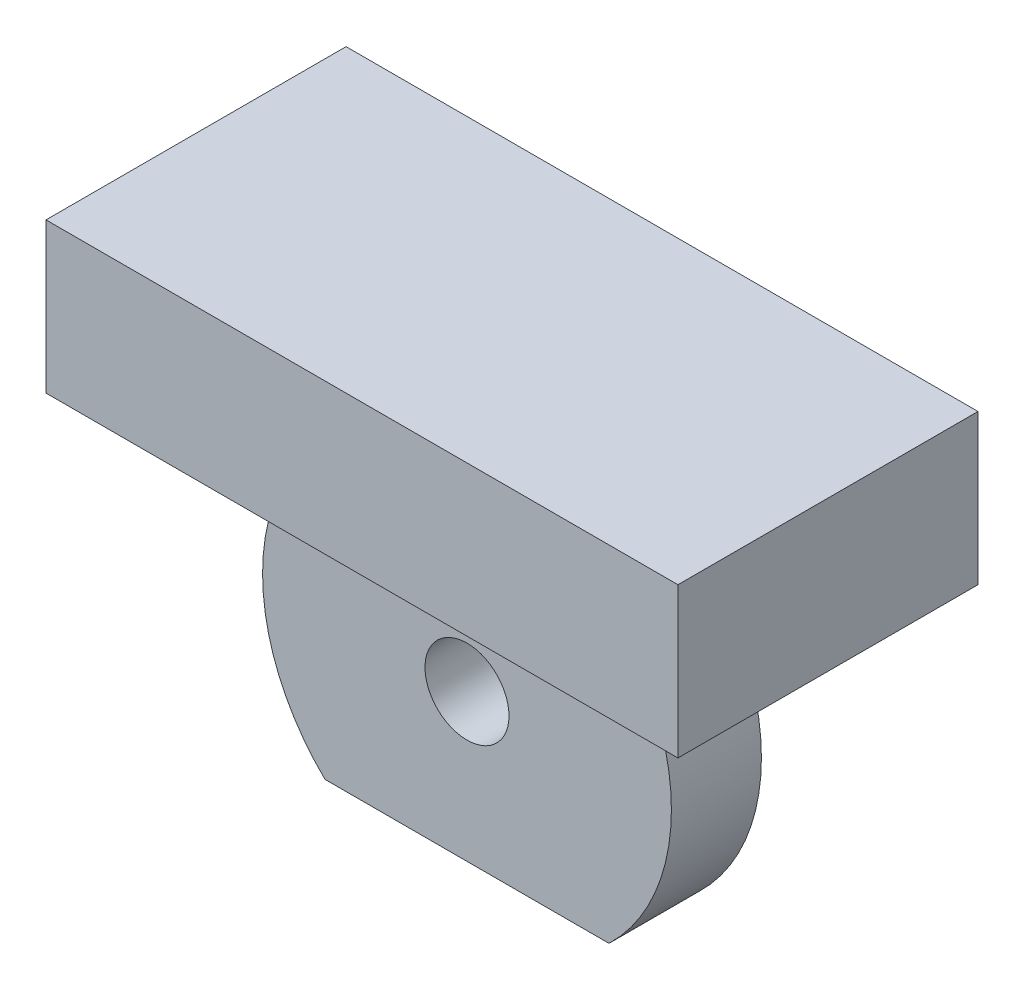
SolidWorks part; units mm, degrees
ref_plane "Front Plane" through (0, 0, 0) normal (0, 0, 1) x (1, 0, 0)
ref_plane "Top Plane" through (0, 0, 0) normal (0, 1, 0) x (1, 0, 0)
ref_plane "Right Plane" through (0, 0, 0) normal (1, 0, 0) x (0, 0, -1)
sketch "Sketch1" plane through (0, 0, 0) normal (0, 0, 1) x (1, 0, 0)
  line L1 (0, 0) -> (42.12, 0)
  line L2 (0, 0) -> (0, -10)
  line L3 (0, -10) -> (42.12, -10)
  line L4 (42.12, 0) -> (42.12, -10)
  dimension "D1" = 10
  dimension "D2" = 42.12
extrude "Boss-Extrude1" add sketch "Sketch1" along normal mid plane 20
sketch "Sketch2" plane through (0, 0, 0) normal (0, 0, 1) x (1, 0, 0)
  line L0 (21.06, 0) -> (21.06, -30) construction
  line L1 (42.12, 0) -> (0, 0) construction
  line L2 (11.595, -30) -> (30.525, -30)
  line L3 (11.5743, -10.42) -> (2.4386, -10.42)
  line L4 (2.4386, -10.42) -> (2.4386, -10)
  line L5 (0, -10) -> (42.12, -10) construction
  line L6 (2.4386, -10) -> (39.6814, -10)
  line L7 (39.6814, -10.42) -> (39.6814, -10)
  line L8 (30.5457, -10.42) -> (39.6814, -10.42)
  arc A0 (11.595, -30) -> (11.5743, -10.42) centre (21.06, -20.2) cw
  arc A1 (30.525, -30) -> (30.5457, -10.42) centre (21.06, -20.2) ccw
  circle A2 centre (21.06, -20.2) radius 2.8
  point P15 (21.06, -10)
  dimension "D3" = 20.2
  dimension "D4" = 0.42
  dimension "D5" = 5.6
  dimension "D1" = 30
  dimension "D2" = 18.93
extrude "Boss-Extrude2" add sketch "Sketch2" along normal mid plane 6
